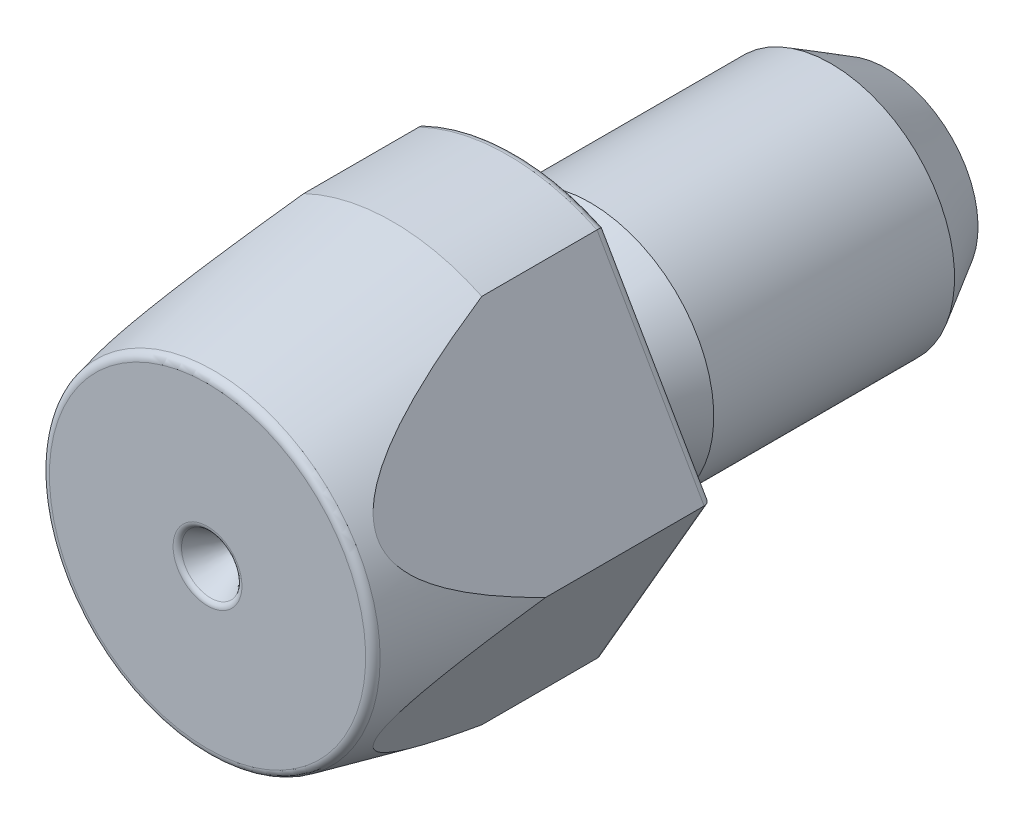
SolidWorks part; units mm, degrees
ref_plane "Front" through (0, 0, 0) normal (0, 0, 1) x (1, 0, 0)
ref_plane "Top" through (0, 0, 0) normal (0, 1, 0) x (1, 0, 0)
ref_plane "Right" through (0, 0, 0) normal (1, 0, 0) x (0, 0, -1)
sketch "Sketch1" plane through (0, 0, 0) normal (1, 0, 0) x (0, 0, -1)
  line L0 (-16.5, 0) -> (16.5, 0) construction
  line L1 (-16.5, -10) -> (-16.5, 10) construction
  line L2 (16.5, -6) -> (16.5, 6) construction
  line L3 (-16.5, 0) -> (-1.5, 0) construction
  line L4 (-16.5, 0) -> (-7.5, 0) construction
  line L5 (16.5, 6) -> (-1.5, 6) construction
  line L6 (-7.5, 10) -> (-16.5, 8.0047) construction
  line L7 (-7.5, 10) -> (-1.5, 10) construction
  line L8 (-1.5, 10) -> (-1.5, 6) construction
  point P3 (-1.5, -6)
  point P4 (0, 0)
  point P7 (-16.5, 0)
  point P11 (16.5, 0)
  point P14 (-7.5, 10)
  point P18 (-16.5, 8.0047)
  point P19 (-1.5, 10)
  point P20 (-1.5, 6)
  point P21 (-1.5, -10)
  point P22 (-7.5, -10)
  point P23 (-16.5, -8.0047)
  dimension "Overall Height" = 33
  dimension "Head Diameter" = 20
  dimension "Shank Diameter" = 12
  dimension "Head Height" = 15
  dimension "Head End Height" = 9
  dimension "D1" = 12.5
  dimension "D2" = 18
sketch "Sketch2" plane through (0, 0, 0) normal (0, 0, 1) x (1, 0, 0)
  line L0 (-9.5318, 0) -> (-4.3266, 9.0156) construction
  line L1 (-9.5318, 0) -> (-4.3266, -9.0156) construction
  line L2 (4.3266, 9.0156) -> (9.5318, 0) construction
  line L3 (9.5318, 0) -> (4.3266, -9.0156) construction
  line L4 (-9.5318, 0) -> (9.5318, 0) construction
  line L5 (7.1488, 4.1274) -> (6.9323, 4.0024) construction
  line L6 (3.9355, 9.193) -> (9.2431, 0) construction
  circle A0 centre (0, 0) radius 10 construction
  circle A1 centre (0, 0) radius 1.5 construction
  circle A2 centre (0, 0) radius 9.5318 construction
  circle A3 centre (0, 0) radius 8.0047 construction
  point P13 (0, 0)
  dimension "D2" = 3
  dimension "D1" = 60
  dimension "D3" = 0.25
sketch "Sketch3" plane through (0, 0, 0) normal (1, 0, 0) x (0, 0, -1)
  line L0 (-16.5, 0) -> (-16.5, 8.0047)
  line L1 (-16.5, 8.0047) -> (-7.5, 10)
  line L2 (-7.5, 10) -> (-1.5, 10)
  line L3 (-1.5, 10) -> (-1.5, 6)
  line L4 (-1.5, 6) -> (16.5, 6)
  line L5 (16.5, 6) -> (16.5, 0)
  line L6 (16.5, 0) -> (-16.5, 0)
  line L7 (16.5, 6) -> (-1.5, 6) construction
revolve "Revolve2" add sketch "Sketch3" angle 360 about L6
sketch "Sketch14" plane through (0, 0, 1.5) normal (0, 0, -1) x (-1, 0, 0)
  line L0 (-9.5318, 0) -> (-4.3266, -9.0156) construction
  line L1 (-4.3266, 9.0156) -> (-9.5318, 0) construction
  line L2 (-9.5318, 0) -> (-4.3266, -9.0156)
  line L3 (-4.3266, 9.0156) -> (-9.5318, 0)
  line L5 (-12.5318, 18.0311) -> (-12.5318, -18.0311)
  line L7 (-4.3266, 9.0156) -> (0.8785, 18.0311)
  line L8 (0.8785, 18.0311) -> (-12.5318, 18.0311)
  line L9 (9.5318, 0) -> (-9.5318, 0) construction
  line L10 (-9.5318, 0) -> (-12.5318, 0) construction
  line L11 (-12.5318, -18.0311) -> (0.8785, -18.0311)
  line L12 (0.8785, -18.0311) -> (-4.3266, -9.0156)
  arc A1 (-4.3266, -9.0156) -> (-4.3266, 9.0156) centre (0, 0) ccw construction
  circle A2 centre (0, 0) radius 10 construction
  dimension "D1" = 3
extrude "Cut-Extrude4" cut sketch "Sketch14" against normal through all
mirror "Mirror1" about plane through (0, 0, 0) normal (1, 0, 0) of "Cut-Extrude4"
sketch "Sketch16" plane through (0, 0, 0) normal (1, 0, 0) x (0, 0, -1)
  line L0 (-1.5, 6) -> (-1.7165, 5.625)
  line L1 (-1.5, 10) -> (-1.5, 6) construction
  line L2 (-1.5, 5.25) -> (-0.2251, 5.25)
  line L3 (0.2879, 5.3405) -> (2.1, 6)
  line L4 (16.5, 6) -> (-1.5, 6) construction
  line L5 (2.1, 6) -> (-1.5, 6)
  line L7 (-1.5, -6) -> (-1.5, 6) construction
  line L8 (16.5, -6) -> (16.5, 6) construction
  line L9 (13.8, 6) -> (16.5, 4.4412)
  line L10 (16.5, 4.4412) -> (16.5, 6)
  line L11 (16.5, 6) -> (13.8, 6)
  line L12 (-1.5, 0) -> (-1.5, 9.0156) construction
  arc A0 (-1.7165, 5.625) -> (-1.5, 5.25) centre (-1.5, 5.5) ccw
  arc A1 (-0.2251, 5.25) -> (0.2879, 5.3405) centre (-0.2251, 6.75) ccw
  dimension "D4" = 1.5
  dimension "D1" = 3.6
  dimension "D2" = 2.7
  dimension "D6" = 20
  dimension "D5" = 0.75
  dimension "D8" = 30
  dimension "D3" = 30
revolve "Cut-Revolve1" cut sketch "Sketch16" angle 360 about L0
sketch "Sketch10" plane through (0, 0, 16.5) normal (0, 0, 1) x (1, 0, 0)
  circle A0 centre (0, 0) radius 1.5 construction
  circle A1 centre (0, 0) radius 1.5
extrude "Cut-Extrude2" cut sketch "Sketch10" against normal blind 3 draft 30
sketch "Sketch15" plane through (0, 0, -16.5) normal (0, 0, -1) x (-1, 0, 0)
  circle A0 centre (0, 0) radius 1.5 construction
  circle A1 centre (0, 0) radius 1.5
extrude "Cut-Extrude5" cut sketch "Sketch15" against normal blind 3 draft 30
fillet "Fillet1" radius 0.4 1 edges at (0, 8.0047, 16.5)
fillet "Fillet2" radius 0.4 6 edges at (6.9292, 4.5078, 1.5) (-6.9292, -4.5078, 1.5) (-6.9292, 4.5078, 1.5) (6.9292, -4.5078, 1.5) (0, -10, 1.5) (0, 10, 1.5)
fillet "Fillet3" radius 0.3 2 edges at (0, 1.5, -16.5) (1.5, 0, 16.5)
equation "\"D2@Sketch2\"=\"Head Diameter@Sketch1\"*.15"
equation "\"D1@Fillet1\"=\"Head Diameter@Sketch1\"*.02"
equation "\"D1@Cut-Extrude2\"=\"Head Diameter@Sketch1\"*.15"
equation "\"D1@Cut-Extrude5\"=\"Head Diameter@Sketch1\"*.15"
equation "\"D1@Sketch16\"=\"D2@Sketch1\"*.2"
equation "\"D2@Sketch16\"=\"D2@Sketch1\"*.15"
equation "\"D5@Sketch16\"=\"Shank Diameter@Sketch1\"*.0625"
equation "\"D4@Sketch16\"=\"D5@Sketch16\"*2"
equation "\"D1@Fillet2\"=\"Head Diameter@Sketch1\"*.02"
equation "\"D1@Fillet3\"=\"D2@Sketch2\"*.1"
equation "\"D3@Sketch2\"=\"Head Diameter@Sketch1\"*.0125"
